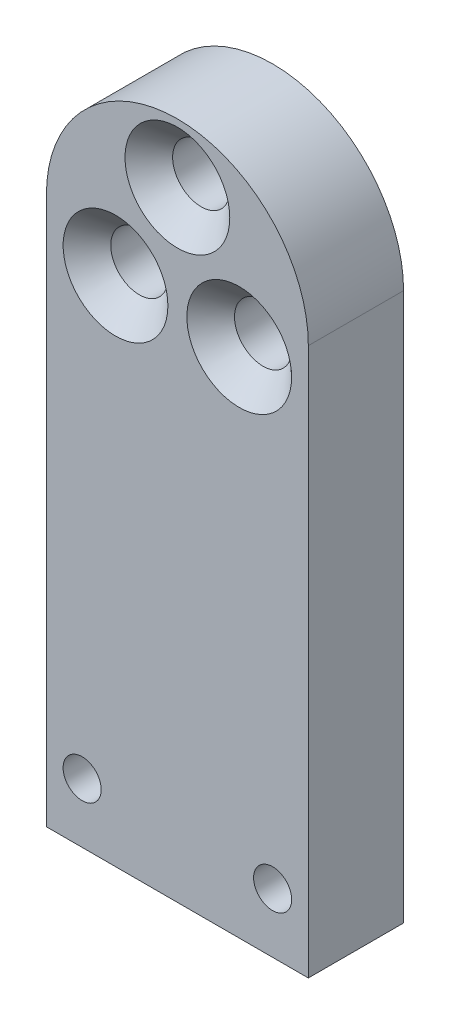
SolidWorks part; units mm, degrees
material "Liga 1060"
ref_plane "Plano frontal" through (0, 0, 0) normal (0, 0, 1) x (1, 0, 0)
ref_plane "Plano superior" through (0, 0, 0) normal (0, 1, 0) x (1, 0, 0)
ref_plane "Plano direito" through (0, 0, 0) normal (1, 0, 0) x (0, 0, -1)
sketch "Esboço1" plane through (0, 0, 0) normal (0, 0, 1) x (1, 0, 0)
  line L0 (-5.5, 0) -> (-5.5, -23)
  line L1 (5.5, 0) -> (5.5, -23)
  line L2 (5.5, -23) -> (-5.5, -23)
  arc A0 (5.5, 0) -> (-5.5, 0) centre (0, 0) ccw
  dimension "D1" = 11
  dimension "D2" = 23
extrude "Ressalto-extrusão1" add sketch "Esboço1" along normal blind 4
sketch "Esboço2" plane through (0, 0, 4) normal (0, 0, 1) x (1, 0, 0)
  circle A0 centre (0, 0) radius 3 construction
  point P3 (0, 3)
  point P11 (0, 0)
  dimension "D1" = 6
sketch "Esboço4" plane through (0, 0, 4) normal (0, 0, 1) x (1, 0, 0)
  line L0 (0, -23) -> (0, -20.5) construction
  line L1 (-5.5, -23) -> (5.5, -23) construction
  line L2 (-4, -20.5) -> (4, -20.5) construction
  dimension "D1" = 2.5
  dimension "D2" = 8
hole_wizard "Furo roscado de M21" positions "3DSketch3" profile "Esboço5" tap size "M2" standard "ISO" end condition through all
sketch3d "3DSketch3"
  point P0 (-4, -20.5, 4)
  point P6 (4, -20.5, 4)
sketch "Esboço5" plane through (-4, -20.5, 4) normal (1, 0, 0) x (0, -1, 0)
  line L0 (0, 0) -> (0, 4)
  line L1 (0, 4) -> (0.8, 4)
  line L2 (0.8, 4) -> (0.8, 0)
  line L5 (0.8, 0) -> (0, 0)
  line L11 (0, -6.35) -> (0, 107.95) construction
  dimension "Thru Tap Drill Dia." = 1.6
  dimension "Thru Tap Drill Depth" = 4
cosmetic thread "Rosca de furo1" parameters "D2"=2
cosmetic thread "Rosca de furo3" parameters "D2"=2
hole_wizard "Escareado para parafuso com cabeça escareada chata de M21" positions "3DSketch4" profile "Esboço6" countersink size "M2" standard "ISO" end condition through all
sketch3d "3DSketch4"
  point P0 (0, 3, 4)
sketch "Esboço6" plane through (0, 3, 4) normal (1, 0, 0) x (0, -1, 0)
  line L0 (0, 0) -> (0, 4)
  line L1 (0, 4) -> (1.2, 4)
  line L2 (1.2, 4) -> (1.2, 1)
  line L3 (1.2, 1) -> (2.2, 0)
  line L5 (2.2, 0) -> (0, 0)
  line L6 (-1.2, 1) -> (-2.2, 0) construction
  line L11 (0, -6.35) -> (0, 107.95) construction
  dimension "Thru Hole Dia." = 2.4
  dimension "Thru Hole Depth" = 4
  dimension "Near C'Sink Dia." = 4.4
  dimension "Near C'Sink Angle" = 90
pattern_circular "PadrãoCircular1" count 3 over 360 about axis through (0, 0, 0) along (0, 0, 1) of "Escareado para parafuso com cabeça escareada chata de M21"
